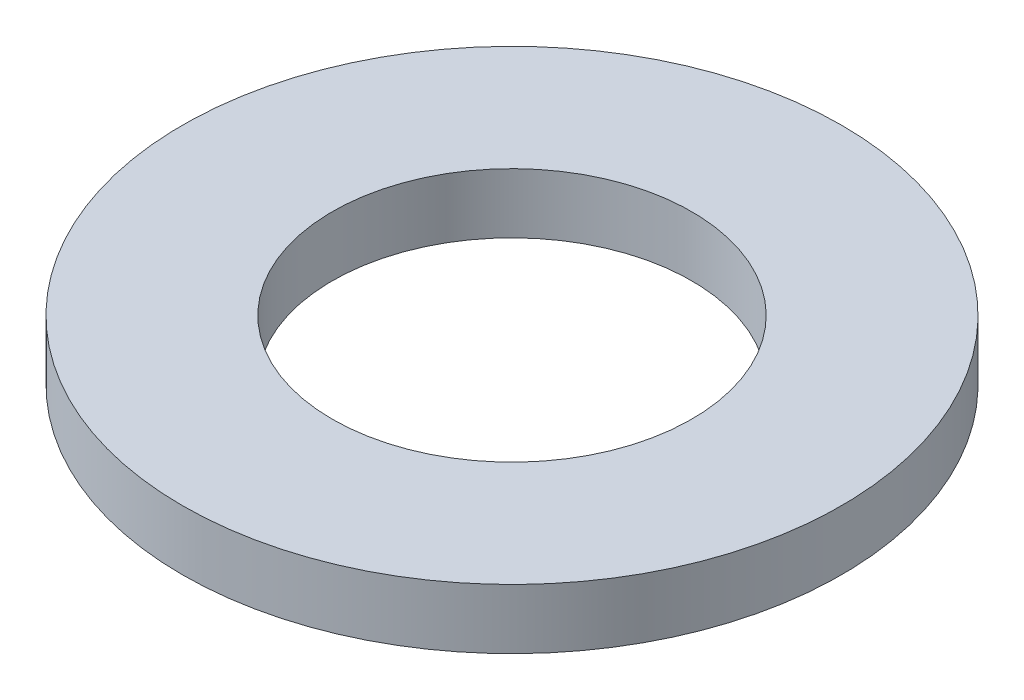
SolidWorks part; units mm, degrees
ref_plane "Front Plane" through (0, 0, 0) normal (0, 0, 1) x (1, 0, 0)
ref_plane "Top Plane" through (0, 0, 0) normal (0, 1, 0) x (1, 0, 0)
ref_plane "Right Plane" through (0, 0, 0) normal (1, 0, 0) x (0, 0, -1)
sketch "Sketch1" plane through (0, 0, 0) normal (0, 1, 0) x (1, 0, 0)
  circle A0 centre (0, 0) radius 11
  circle A1 centre (0, 0) radius 6
  dimension "D1" = 22
  dimension "D2" = 12
extrude "Boss-Extrude1" add sketch "Sketch1" along normal blind 2
